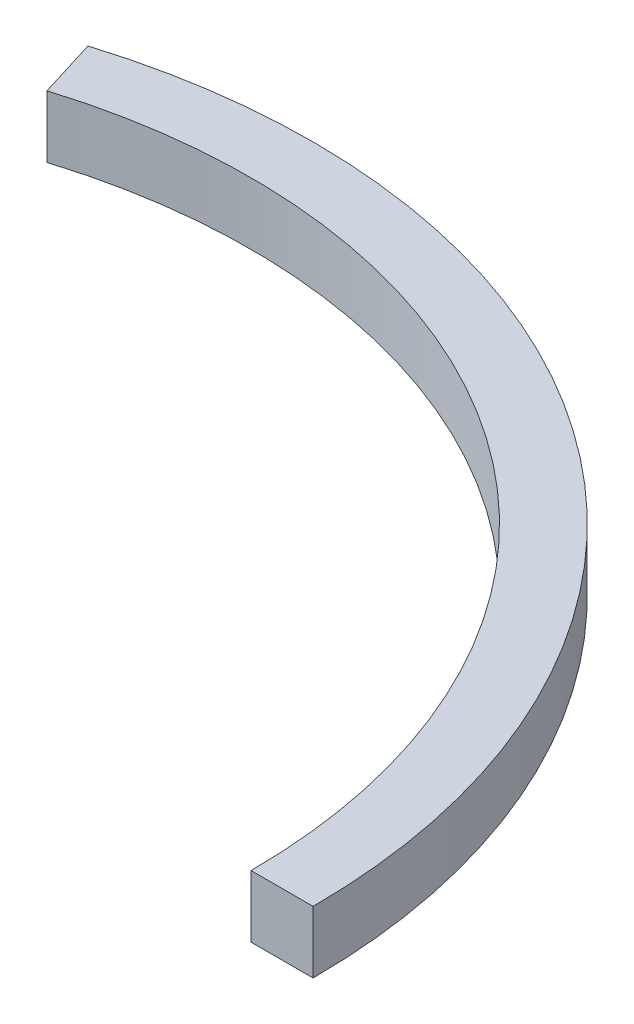
SolidWorks part; units mm, degrees
ref_plane "前视基准面" through (0, 0, 0) normal (0, 0, 1) x (1, 0, 0)
ref_plane "上视基准面" through (0, 0, 0) normal (0, 1, 0) x (1, 0, 0)
ref_plane "右视基准面" through (0, 0, 0) normal (1, 0, 0) x (0, 0, -1)
sketch "Sketch1" plane through (0, 0, 0) normal (0, 0, 1) x (1, 0, 0)
  line L1 (55.1557, -1.1253) -> (50.1557, -1.1253)
  line L2 (55.1557, -1.1253) -> (55.1557, 3.8747)
  line L3 (55.1557, 3.8747) -> (50.1557, 3.8747)
  line L4 (50.1557, -1.1253) -> (50.1557, 3.8747)
  dimension "D1" = 5
  dimension "D2" = 5
sketch "Sketch3" plane through (0, 5.0171, 0) normal (0, 1, 0) x (1, 0, 0)
  arc A1 (42.8002, 0) -> (-10.3133, 39.1697) centre (1.8002, 0) ccw
sweep "Sweep1" add profiles "Sketch1" path "Sketch3"
